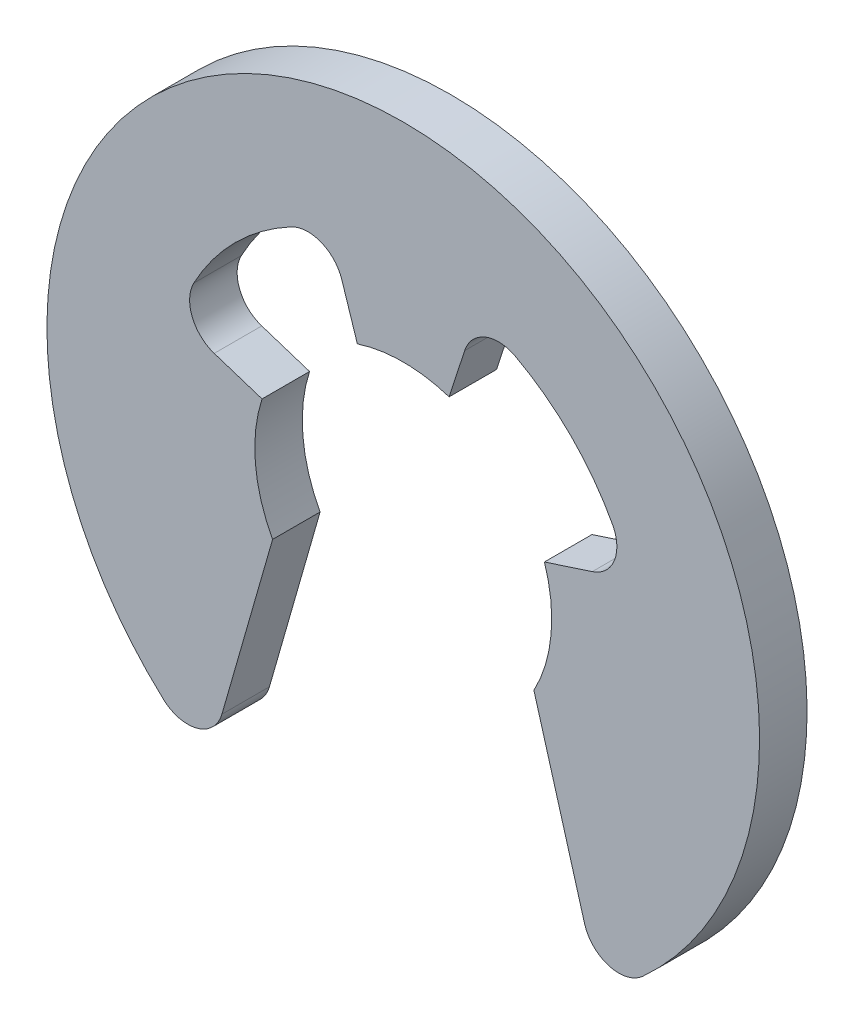
SolidWorks part; units mm, degrees
ref_plane "Front" through (0, 0, 0) normal (0, 0, 1) x (1, 0, 0)
ref_plane "Top" through (0, 0, 0) normal (0, 1, 0) x (1, 0, 0)
ref_plane "Right" through (0, 0, 0) normal (1, 0, 0) x (0, 0, -1)
sketch "Sketch1" plane through (0, 0, 0) normal (0, 0, 1) x (1, 0, 0)
  line L0 (0, 2.1875) -> (0, -1.9262) construction
  line L1 (-1.6904, 0) -> (1.9829, 0) construction
  line L2 (0, 0) -> (0.9271, 2.8532) construction
  line L3 (0, 0) -> (2.8532, 0.9271) construction
  line L4 (0.5171, 1.5914) -> (0.3863, 1.1888)
  line L5 (1.1888, 0.3863) -> (1.5914, 0.5171)
  line L6 (1.1, -0.5937) -> (1.5266, -2.0816)
  line L7 (-1.1888, 0.3863) -> (-1.5914, 0.5171)
  line L8 (-0.5171, 1.5914) -> (-0.3863, 1.1888)
  line L9 (-1.1, -0.5937) -> (-1.5266, -2.0816)
  arc A0 (2.0167, -2.221) -> (-2.0167, -2.221) centre (0, 0) ccw
  arc A1 (1.1, -0.5937) -> (1.1888, 0.3863) centre (0, 0) ccw
  arc A2 (1.7632, 0.944) -> (0.944, 1.7632) centre (0, 0) ccw
  arc A3 (1.7632, 0.944) -> (1.5914, 0.5171) centre (1.4987, 0.8024) cw
  arc A4 (1.5266, -2.0816) -> (2.0167, -2.221) centre (1.815, -1.9989) ccw
  arc A5 (-1.5266, -2.0816) -> (-2.0167, -2.221) centre (-1.815, -1.9989) cw
  arc A6 (0.3863, 1.1888) -> (-0.3863, 1.1888) centre (0, 0) ccw
  arc A7 (0.5171, 1.5914) -> (0.944, 1.7632) centre (0.8024, 1.4987) cw
  arc A8 (-1.1, -0.5937) -> (-1.1888, 0.3863) centre (0, 0) cw
  arc A9 (-1.7632, 0.944) -> (-1.5914, 0.5171) centre (-1.4987, 0.8024) ccw
  arc A10 (-0.5171, 1.5914) -> (-0.944, 1.7632) centre (-0.8024, 1.4987) ccw
  arc A11 (-1.7632, 0.944) -> (-0.944, 1.7632) centre (0, 0) cw
  point P17 (1.9021, 0.618)
  point P25 (0.618, 1.9021)
  dimension "D0" = 6
  dimension "d" = 2.5
  dimension "r2" = 0.3
  dimension "r1" = 0.3
  dimension "R" = 2
  dimension "D2" = 18
  dimension "D3" = 18
  dimension "D4" = 16
  dimension "B" = 2.2
extrude "Body" add sketch "Sketch1" against normal blind 0.4
equation "\"r2@Sketch1\" = \"r1@Sketch1\""
